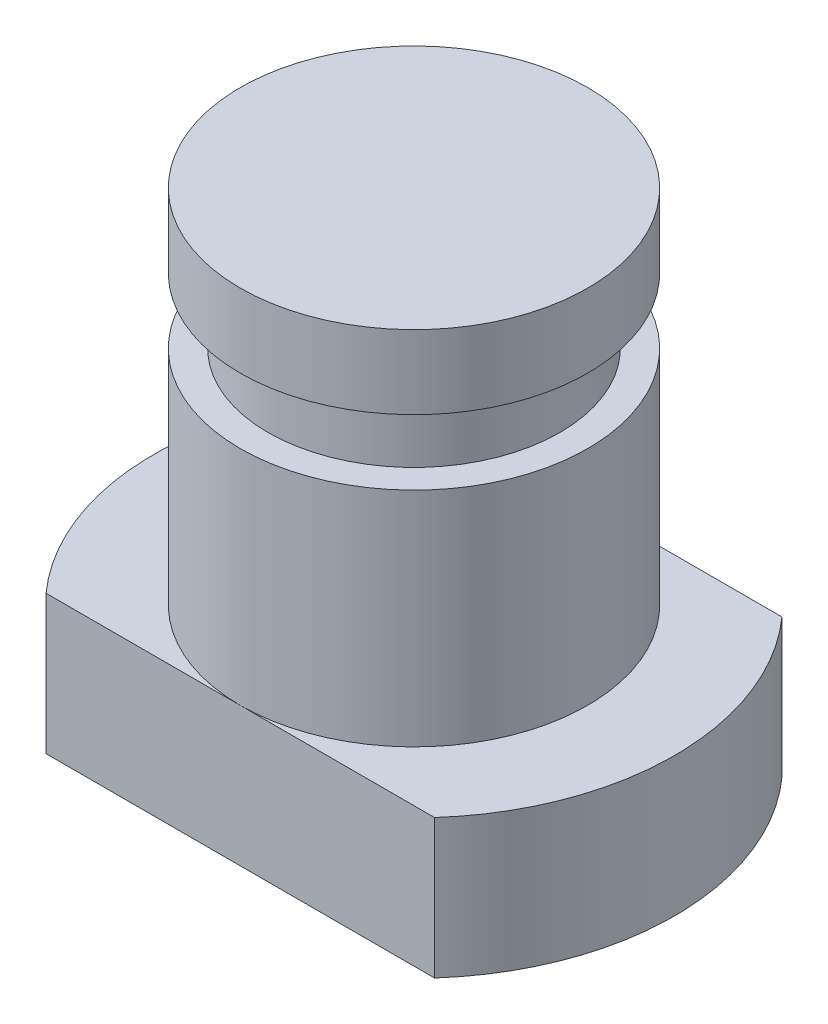
SolidWorks part; units mm, degrees
material "AISI 1015 Steel, Cold Drawn (SS)"
ref_plane "Front Plane" through (0, 0, 0) normal (0, 0, 1) x (1, 0, 0)
ref_plane "Top Plane" through (0, 0, 0) normal (0, 1, 0) x (1, 0, 0)
ref_plane "Right Plane" through (0, 0, 0) normal (1, 0, 0) x (0, 0, -1)
sketch "Sketch1" plane through (0, 0, 0) normal (0, 1, 0) x (1, 0, 0)
  circle A0 centre (0, 0) radius 3.175
  dimension "D1" = 6.35
extrude "Boss-Extrude1" add sketch "Sketch1" along normal blind 6.604
sketch "Sketch2" plane through (0, 0, 0) normal (0, -1, 0) x (1, 0, 0)
  line L0 (-10.6761, 0) -> (14.4716, 0) construction
  line L1 (-3.5498, 3.175) -> (3.5498, 3.175)
  line L2 (-3.5498, -3.175) -> (3.5498, -3.175)
  circle A2 centre (0, 0) radius 3.175 construction
  arc A3 (-3.5498, 3.175) -> (-3.5498, -3.175) centre (0, 0) ccw
  arc A4 (3.5498, -3.175) -> (3.5498, 3.175) centre (0, 0) ccw
  dimension "D1" = 9.525
extrude "Boss-Extrude2" add sketch "Sketch2" along normal blind 2.54
ref_plane "Plane1" through (0, 4.064, 0) normal (0, 1, 0) x (1, 0, 0)
sketch "Sketch6" plane through (0, 4.064, 0) normal (0, 1, 0) x (1, 0, 0)
  circle A0 centre (0, 0) radius 2.667
  dimension "D1" = 5.334
extrude "Cut-Extrude1" cut sketch "Sketch6" along normal blind 1.1938 flip side to cut
equation "\"0.3n\"=0.4"
